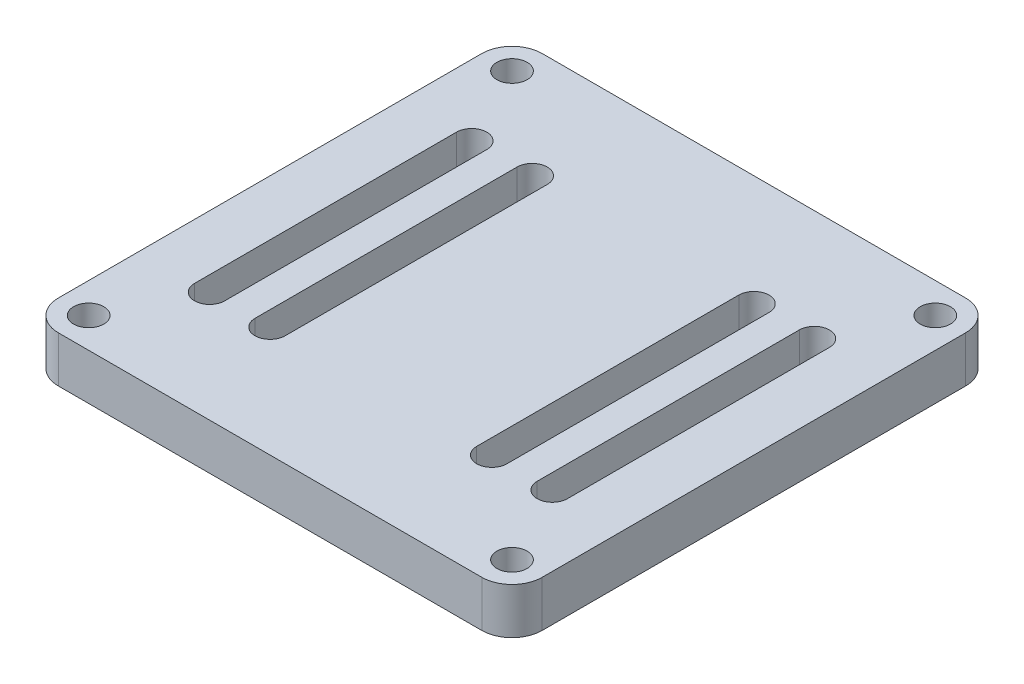
SolidWorks part; units mm, degrees
ref_plane "Front Plane" through (0, 0, 0) normal (0, 0, 1) x (1, 0, 0)
ref_plane "Top Plane" through (0, 0, 0) normal (0, 1, 0) x (1, 0, 0)
ref_plane "Right Plane" through (0, 0, 0) normal (1, 0, 0) x (0, 0, -1)
sketch "Sketch3" plane through (0, 0, 0) normal (0, 1, 0) x (1, 0, 0)
  line L0 (-14.4411, 24) -> (61.8307, 24) construction
  line L1 (3, 0) -> (45, 0)
  line L2 (0, 3) -> (0, 45)
  line L3 (3, 48) -> (45, 48)
  line L4 (48, 3) -> (48, 45)
  line L5 (24, 63.2088) -> (24, -13.6353) construction
  line L6 (4, 61.6313) -> (4, -6.5378) construction
  line L7 (44, 55.0612) -> (44, -10.615) construction
  line L8 (7, 37) -> (7, 11) construction
  line L9 (10, 67.0686) -> (10, -12.2183) construction
  line L10 (8.5, 37) -> (8.5, 11)
  line L11 (5.5, 37) -> (5.5, 11)
  line L12 (13, 37) -> (13, 11) construction
  line L13 (11.5, 37) -> (11.5, 11)
  line L14 (14.5, 37) -> (14.5, 11)
  line L15 (35, 37) -> (35, 11) construction
  line L16 (36.5, 37) -> (36.5, 11)
  line L17 (33.5, 37) -> (33.5, 11)
  line L18 (41, 37) -> (41, 11) construction
  line L19 (39.5, 37) -> (39.5, 11)
  line L20 (42.5, 37) -> (42.5, 11)
  circle A0 centre (3, 45) radius 1.5
  circle A1 centre (3, 3) radius 1.5
  circle A2 centre (45, 3) radius 1.5
  circle A3 centre (45, 45) radius 1.5
  arc A4 (3, 0) -> (0, 3) centre (3, 3) cw
  arc A5 (45, 0) -> (48, 3) centre (45, 3) ccw
  arc A6 (45, 48) -> (48, 45) centre (45, 45) cw
  arc A7 (0, 45) -> (3, 48) centre (3, 45) cw
  arc A8 (8.5, 37) -> (5.5, 37) centre (7, 37) ccw
  arc A9 (5.5, 11) -> (8.5, 11) centre (7, 11) ccw
  arc A10 (11.5, 37) -> (14.5, 37) centre (13, 37) cw
  arc A11 (14.5, 11) -> (11.5, 11) centre (13, 11) cw
  arc A12 (36.5, 37) -> (33.5, 37) centre (35, 37) ccw
  arc A13 (33.5, 11) -> (36.5, 11) centre (35, 11) ccw
  arc A14 (39.5, 37) -> (42.5, 37) centre (41, 37) cw
  arc A15 (42.5, 11) -> (39.5, 11) centre (41, 11) cw
  point P20 (0, 0)
  point P27 (0, 48)
  point P35 (7, 24)
  point P44 (13, 24)
  point P51 (35, 24)
  point P58 (41, 24)
  dimension "D2" = 3
  dimension "D6" = 3
  dimension "D7" = 3
  dimension "D1" = 48
  dimension "D3" = 3
  dimension "D4" = 24
  dimension "D5" = 24
  dimension "D8" = 4
  dimension "D9" = 4
  dimension "D10" = 3
  dimension "D11" = 29
  dimension "D12" = 7
  dimension "D13" = 1.5
extrude "Boss-Extrude1" add sketch "Sketch3" along normal blind 4.572
